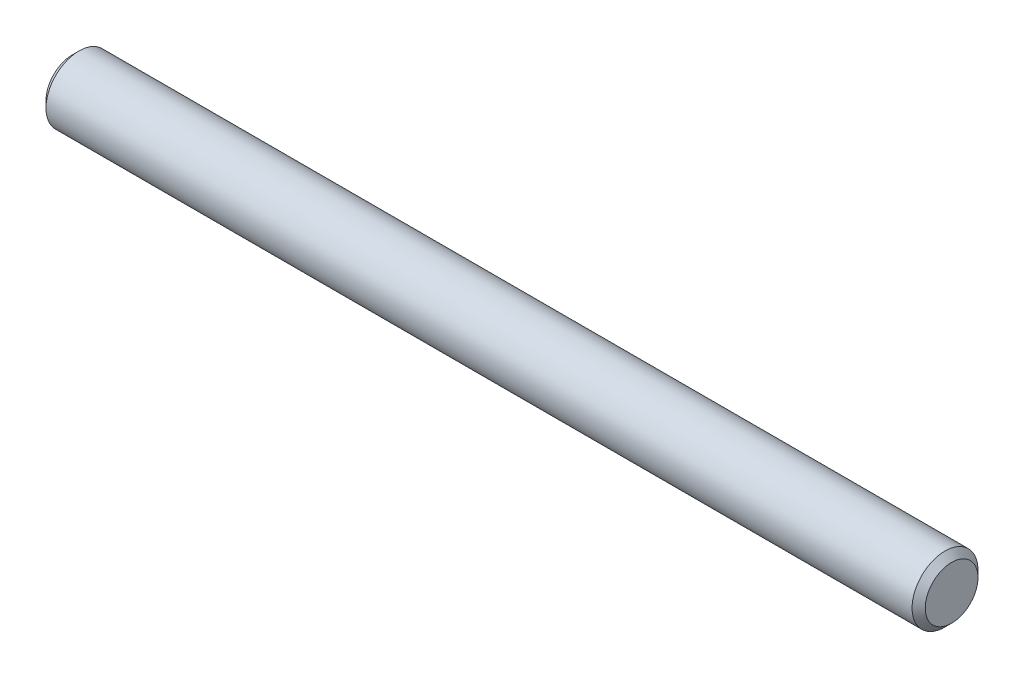
SolidWorks part; units mm, degrees
ref_plane "前视基准面" through (0, 0, 0) normal (0, 0, 1) x (1, 0, 0)
ref_plane "上视基准面" through (0, 0, 0) normal (0, 1, 0) x (1, 0, 0)
ref_plane "右视基准面" through (0, 0, 0) normal (1, 0, 0) x (0, 0, -1)
sketch "草图1" plane through (0, 0, 0) normal (1, 0, 0) x (0, 0, -1)
  circle A0 centre (0, 0) radius 1.5
  dimension "D1" = 3
extrude "凸台-拉伸1" add sketch "草图1" along normal mid plane 40
chamfer "倒角1" distance 0.3 angle 45 2 edges at (-20, 0, -1.5) (20, 0, -1.5)
